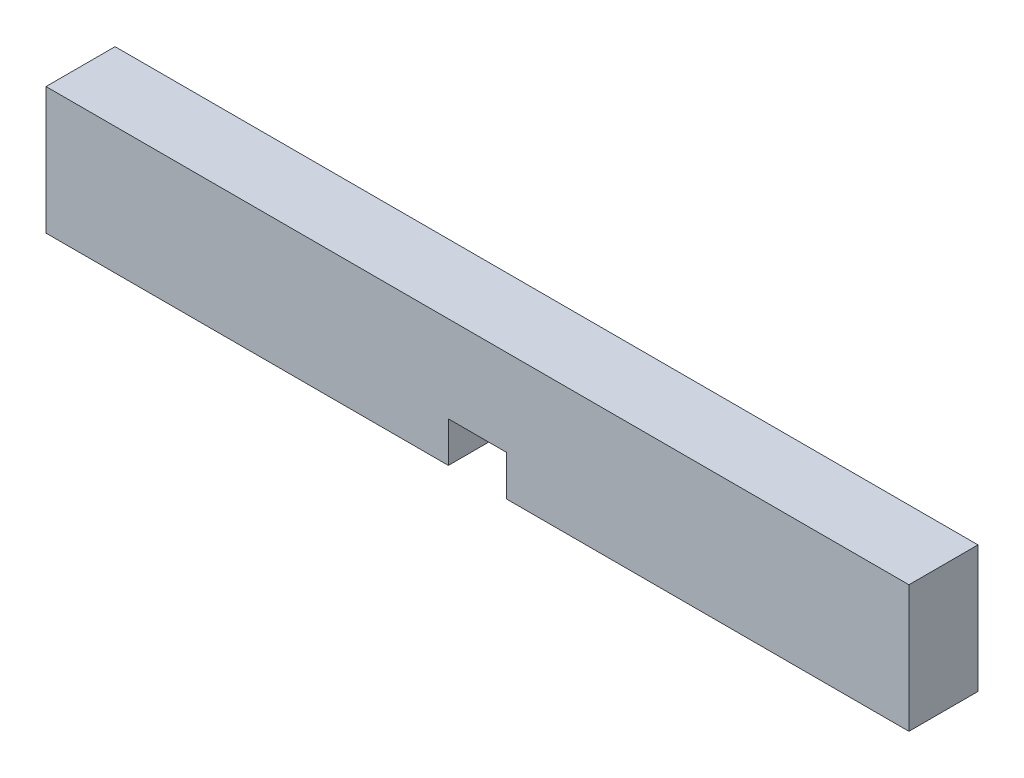
SolidWorks part; units mm, degrees
material "Cast Alloy Steel"
ref_plane "Front Plane" through (0, 0, 0) normal (0, 0, 1) x (1, 0, 0)
ref_plane "Top Plane" through (0, 0, 0) normal (0, 1, 0) x (1, 0, 0)
ref_plane "Right Plane" through (0, 0, 0) normal (1, 0, 0) x (0, 0, -1)
sketch "Sketch1" plane through (0, 0, 0) normal (0, 0, 1) x (1, 0, 0)
  line L0 (-1.98, -4.32) -> (-1.98, -1.5718)
  line L1 (-29.36, 4.32) -> (29.36, 4.32)
  line L2 (-29.36, 4.32) -> (-29.36, -4.32)
  line L3 (-29.36, -4.32) -> (-1.98, -4.32)
  line L4 (29.36, 4.32) -> (29.36, -4.32)
  line L7 (-1.98, -1.5718) -> (1.98, -1.5718)
  line L8 (1.98, -1.5718) -> (1.98, -4.32)
  line L9 (0, 0) -> (0, -1.5718)
  line L10 (1.98, -4.32) -> (29.36, -4.32)
  point P0 (0, 0)
  dimension "D1" = 8.64
  dimension "D2" = 58.72
  dimension "D3" = 27.38
extrude "Boss-Extrude1" add sketch "Sketch1" along normal mid plane 4.7
